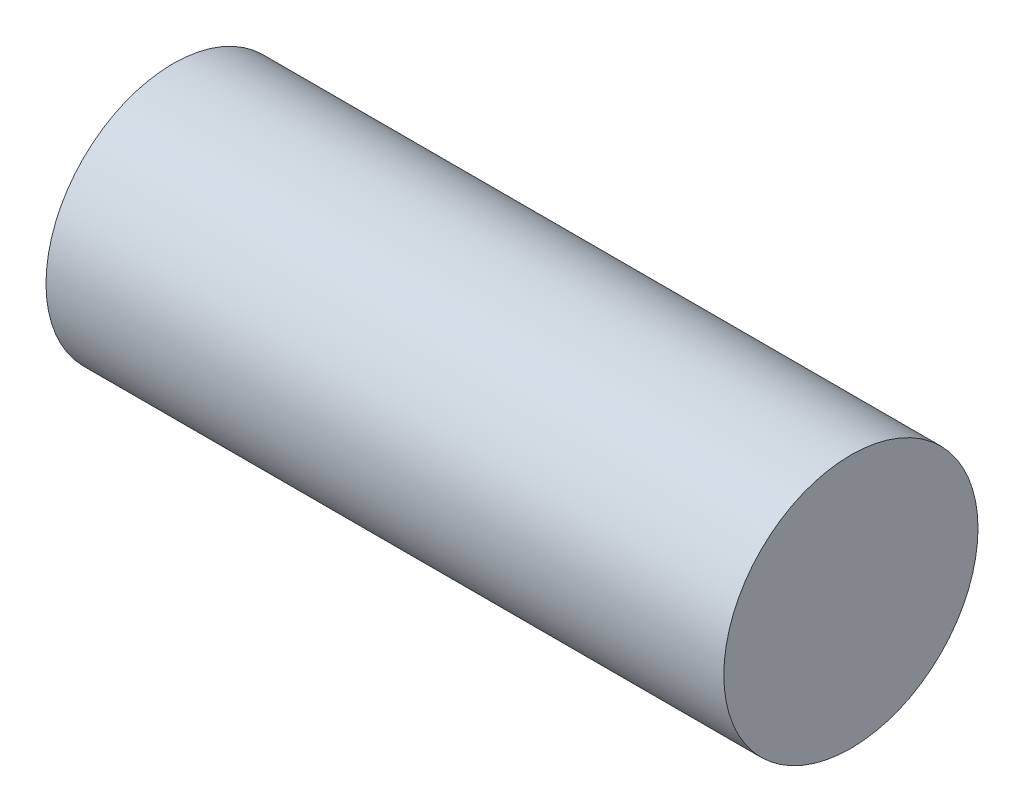
SolidWorks part; units mm, degrees
ref_plane "Front Plane" through (0, 0, 0) normal (0, 0, 1) x (1, 0, 0)
ref_plane "Top Plane" through (0, 0, 0) normal (0, 1, 0) x (1, 0, 0)
ref_plane "Right Plane" through (0, 0, 0) normal (1, 0, 0) x (0, 0, -1)
sketch "Sketch1" plane through (0, 0, 0) normal (1, 0, 0) x (0, 0, -1)
  circle A0 centre (0, 0) radius 38.1
  dimension "D1" = 76.2
extrude "Boss-Extrude1" add sketch "Sketch1" along normal mid plane 203.2
